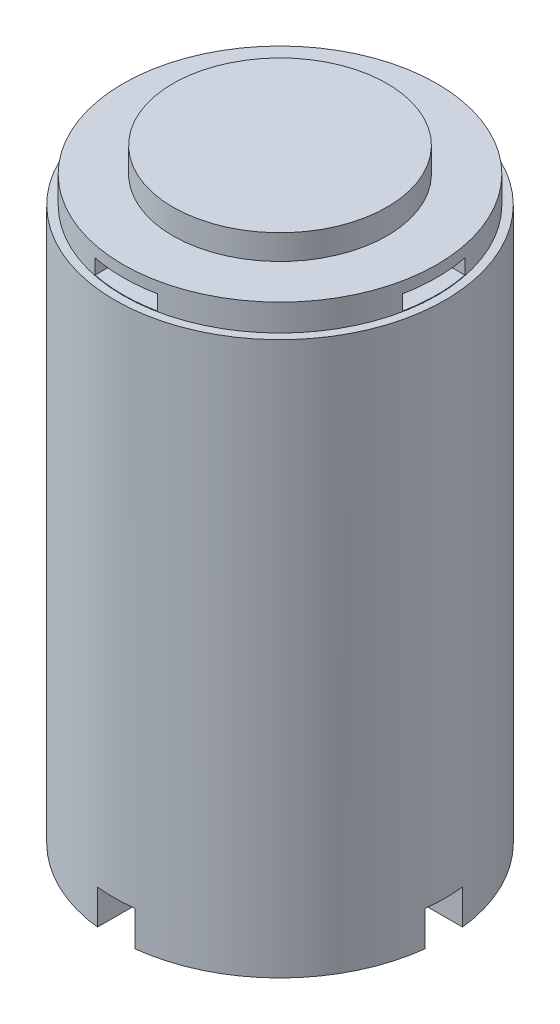
SolidWorks part; units mm, degrees
material "AISI 304"
ref_plane "Front" through (0, 0, 0) normal (0, 0, 1) x (1, 0, 0)
ref_plane "Top" through (0, 0, 0) normal (0, 1, 0) x (1, 0, 0)
ref_plane "Right" through (0, 0, 0) normal (1, 0, 0) x (0, 0, -1)
sketch "Sketch1" plane through (0, 0, 0) normal (0, 1, 0) x (1, 0, 0)
  line L0 (0, 0) -> (0, -1682.75) construction
  circle A0 centre (0, 0) radius 1682.75
  point P3 (0, -1682.75)
  dimension "D1" = 3365.5
extrude "Boss-Extrude1" add sketch "Sketch1" along normal blind 5588 contours A0
sketch "Sketch2" plane through (0, 5588, 0) normal (0, 1, 0) x (1, 0, 0)
  circle A0 centre (0, 0) radius 1600.2
  dimension "D1" = 3200.4
extrude "Boss-Extrude2" add sketch "Sketch2" along normal blind 273.05
sketch "Sketch3" plane through (0, 5861.05, 0) normal (0, 1, 0) x (1, 0, 0)
  circle A0 centre (0, 0) radius 1092.2
  dimension "D1" = 2184.4
extrude "Boss-Extrude3" add sketch "Sketch3" along normal blind 254
ref_plane "Plane1" through (-1682.75, 0, 0) normal (-1, 0, 0) x (0, 0, 1)
sketch "Sketch4" plane through (-1682.75, 0, 0) normal (-1, 0, 0) x (0, 0, 1)
  line L0 (-1682.75, 0) -> (1682.75, 0) construction
  line L1 (-190.5, 0) -> (190.5, 0)
  line L2 (-190.5, 0) -> (-190.5, 304.8)
  line L3 (-190.5, 304.8) -> (190.5, 304.8)
  line L4 (190.5, 0) -> (190.5, 304.8)
  line L5 (0, 0) -> (0, 304.8) construction
  dimension "D1" = 381
  dimension "D2" = 304.8
extrude "Cut-Extrude1" cut sketch "Sketch4" against normal through all
pattern_circular "CirPattern1" count 2 every 90 about axis through (0, 5588, 0) along (0, -1, 0) of "Cut-Extrude1"
sketch "Sketch5" plane through (-1682.75, 0, 0) normal (-1, 0, 0) x (0, 0, 1)
  line L0 (1682.75, 5588) -> (-1682.75, 5588) construction
  line L1 (-317.5, 5594.35) -> (317.5, 5594.35)
  line L2 (-317.5, 5594.35) -> (-317.5, 5746.75)
  line L3 (-317.5, 5746.75) -> (317.5, 5746.75)
  line L4 (317.5, 5594.35) -> (317.5, 5746.75)
  line L5 (0, 0) -> (0, 5594.35) construction
  dimension "D1" = 6.35
  dimension "D2" = 635
  dimension "D3" = 152.4
extrude "Cut-Extrude2" cut sketch "Sketch5" against normal through all
pattern_circular "CirPattern2" count 2 every 90 about axis through (0, 5588, 0) along (0, -1, 0) of "Cut-Extrude2"
sketch "Sketch6" plane through (0, 0, 0) normal (0, -1, 0) x (1, 0, 0)
  line L0 (-190.5, 1671.9322) -> (-190.5, 1294.1543)
  line L1 (-190.5, 190.5) -> (-190.5, 1671.9322) construction
  line L2 (-1671.9322, 190.5) -> (-1294.1543, 190.5)
  line L3 (190.5, 1671.9322) -> (190.5, 190.5) construction
  line L4 (190.5, 1294.1543) -> (190.5, 1671.9322)
  line L5 (-1671.9322, -190.5) -> (-1294.1543, -190.5)
  line L6 (-190.5, -190.5) -> (-1671.9322, -190.5) construction
  line L7 (-190.5, -1671.9322) -> (-190.5, -1294.1543)
  line L8 (-190.5, -1671.9322) -> (-190.5, -190.5) construction
  line L9 (190.5, -1671.9322) -> (190.5, -1294.1543)
  line L10 (190.5, -190.5) -> (190.5, -1671.9322) construction
  line L11 (1294.1543, 190.5) -> (1671.9322, 190.5)
  line L12 (1671.9322, 190.5) -> (190.5, 190.5) construction
  line L13 (1671.9322, -190.5) -> (1294.1543, -190.5)
  line L14 (1671.9322, -190.5) -> (190.5, -190.5) construction
  arc A0 (-1671.9322, -190.5) -> (-190.5, -1671.9322) centre (0, 0) ccw construction
  arc A1 (190.5, -1671.9322) -> (1671.9322, -190.5) centre (0, 0) ccw construction
  arc A2 (1671.9322, 190.5) -> (190.5, 1671.9322) centre (0, 0) ccw construction
  arc A3 (-190.5, 1671.9322) -> (-1671.9322, 190.5) centre (0, 0) ccw construction
  arc A4 (-1671.9322, -190.5) -> (-190.5, -1671.9322) centre (0, 0) ccw
  arc A5 (190.5, -1671.9322) -> (1671.9322, -190.5) centre (0, 0) ccw
  arc A6 (1671.9322, 190.5) -> (190.5, 1671.9322) centre (0, 0) ccw
  arc A7 (-190.5, 1671.9322) -> (-1671.9322, 190.5) centre (0, 0) ccw
  arc A8 (-190.5, -1294.1543) -> (190.5, -1294.1543) centre (0, 0) ccw
  arc A9 (-1294.1543, 190.5) -> (-1294.1543, -190.5) centre (0, 0) ccw
  arc A10 (190.5, 1294.1543) -> (-190.5, 1294.1543) centre (0, 0) ccw
  arc A11 (1294.1543, -190.5) -> (1294.1543, 190.5) centre (0, 0) ccw
  dimension "D1" = 2616.2
extrude "Boss-Extrude4" add sketch "Sketch6" along normal blind 50.8
